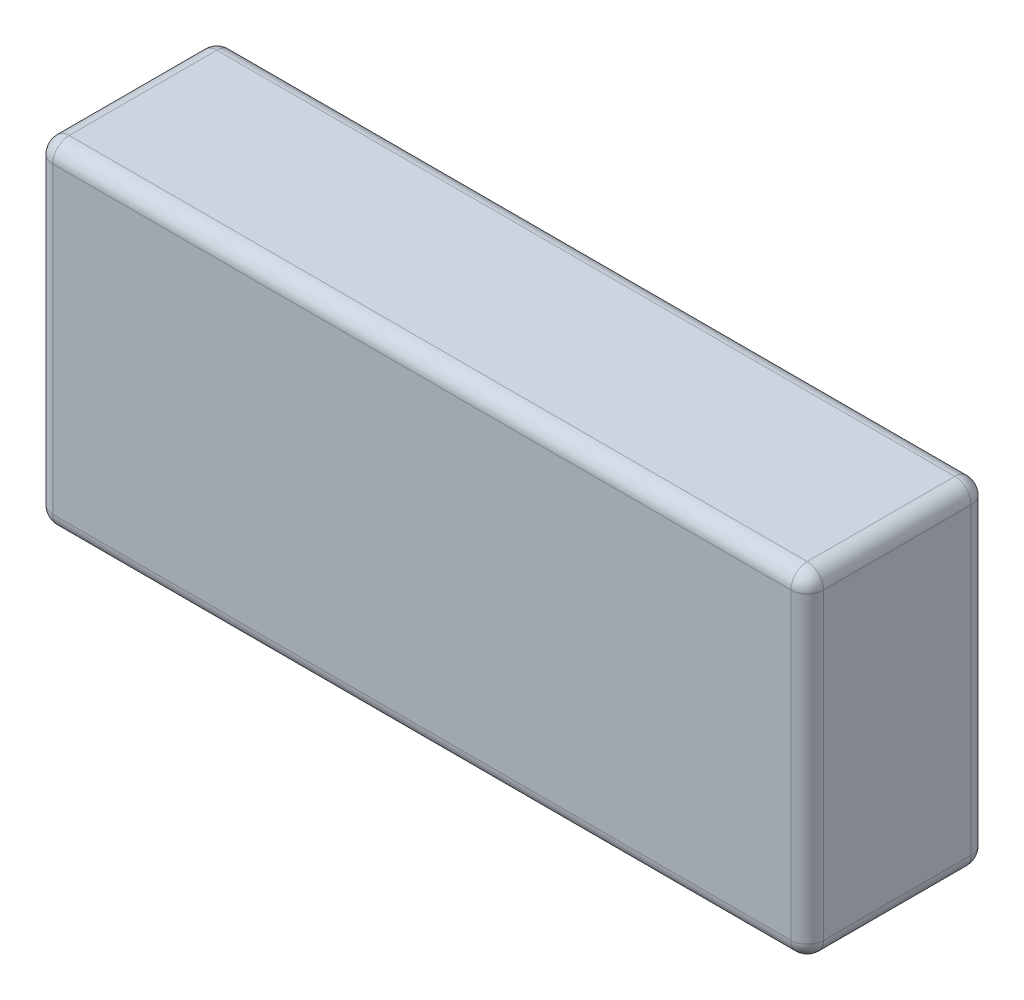
SolidWorks part; units mm, degrees
ref_plane "前视基准面" through (0, 0, 0) normal (0, 0, 1) x (1, 0, 0)
ref_plane "上视基准面" through (0, 0, 0) normal (0, 1, 0) x (1, 0, 0)
ref_plane "右视基准面" through (0, 0, 0) normal (1, 0, 0) x (0, 0, -1)
sketch "草图1" plane through (0, 0, 0) normal (0, 0, 1) x (1, 0, 0)
  line L1 (-61.0632, 27.5132) -> (32.9368, 27.5132)
  line L2 (-61.0632, 27.5132) -> (-61.0632, -13.4868)
  line L3 (-61.0632, -13.4868) -> (32.9368, -13.4868)
  line L4 (32.9368, 27.5132) -> (32.9368, -13.4868)
  line L5 (-61.0632, 27.5132) -> (32.9368, -13.4868) construction
  line L6 (-61.0632, -13.4868) -> (32.9368, 27.5132) construction
  point P0 (-14.0632, 7.0132)
  dimension "D1" = 41
  dimension "D2" = 94
extrude "凸台-拉伸1" add sketch "草图1" along normal blind 22
fillet "圆角1" radius 2 12 edges at (-14.0632, -13.4868, 0) (-61.0632, -13.4868, 11) (-61.0632, 7.0132, 0) (-61.0632, 27.5132, 11) (-14.0632, 27.5132, 0) (32.9368, -13.4868, 11) (32.9368, 27.5132, 11) (32.9368, 7.0132, 0) (-14.0632, -13.4868, 22) (-61.0632, 7.0132, 22) (-14.0632, 27.5132, 22) (32.9368, 7.0132, 22)
